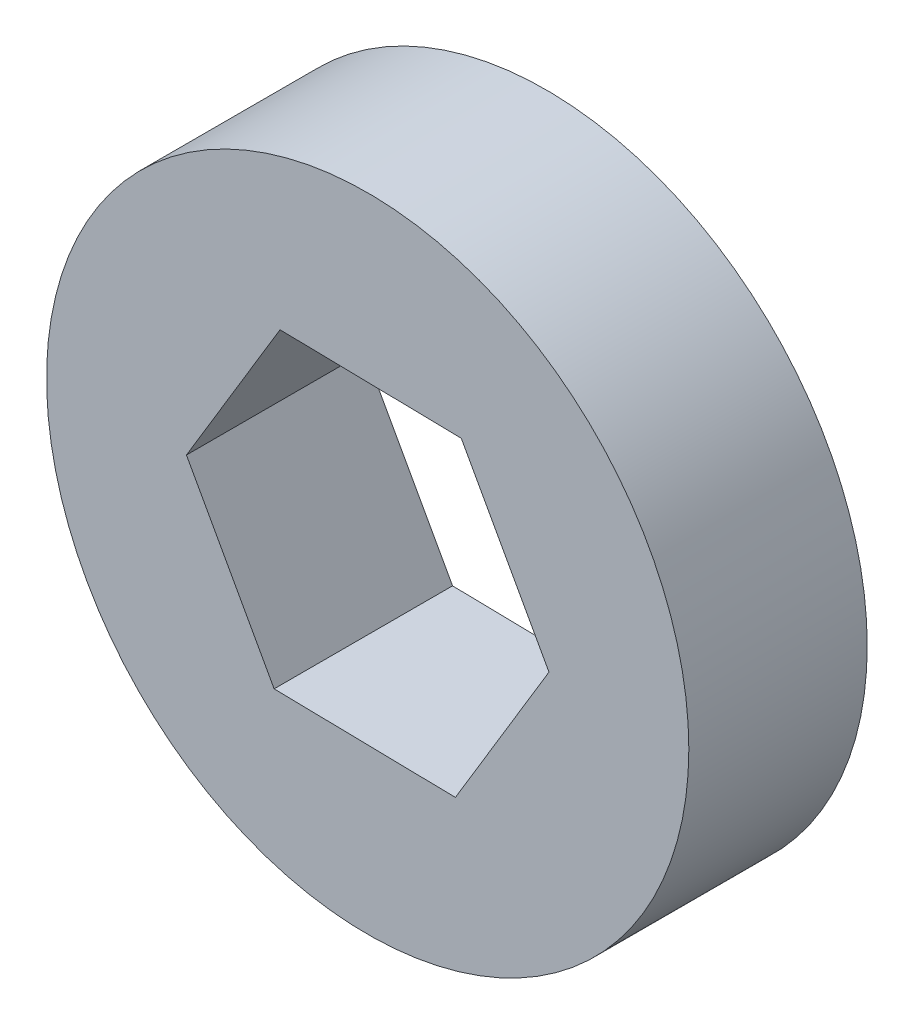
SolidWorks part; units mm, degrees
ref_plane "Front Plane" through (0, 0, 0) normal (0, 0, 1) x (1, 0, 0)
ref_plane "Top Plane" through (0, 0, 0) normal (0, 1, 0) x (1, 0, 0)
ref_plane "Right Plane" through (0, 0, 0) normal (1, 0, 0) x (0, 0, -1)
sketch "Sketch1" plane through (0, 0, 0) normal (0, 0, 1) x (1, 0, 0)
  line L1 (-3.3302, -5.5267) -> (3.1212, -5.6474)
  line L2 (3.1212, -5.6474) -> (6.4513, -0.1207)
  line L3 (6.4513, -0.1207) -> (3.3302, 5.5267)
  line L4 (3.3302, 5.5267) -> (-3.1212, 5.6474)
  line L5 (-3.1212, 5.6474) -> (-6.4513, 0.1207)
  line L6 (-6.4513, 0.1207) -> (-3.3302, -5.5267)
  circle A0 centre (0, 0) radius 11.43
  circle A1 centre (0, 0) radius 5.588 construction
  dimension "D1" = 22.86
  dimension "D2" = 11.176
extrude "Boss-Extrude1" add sketch "Sketch1" along normal blind 6.35
